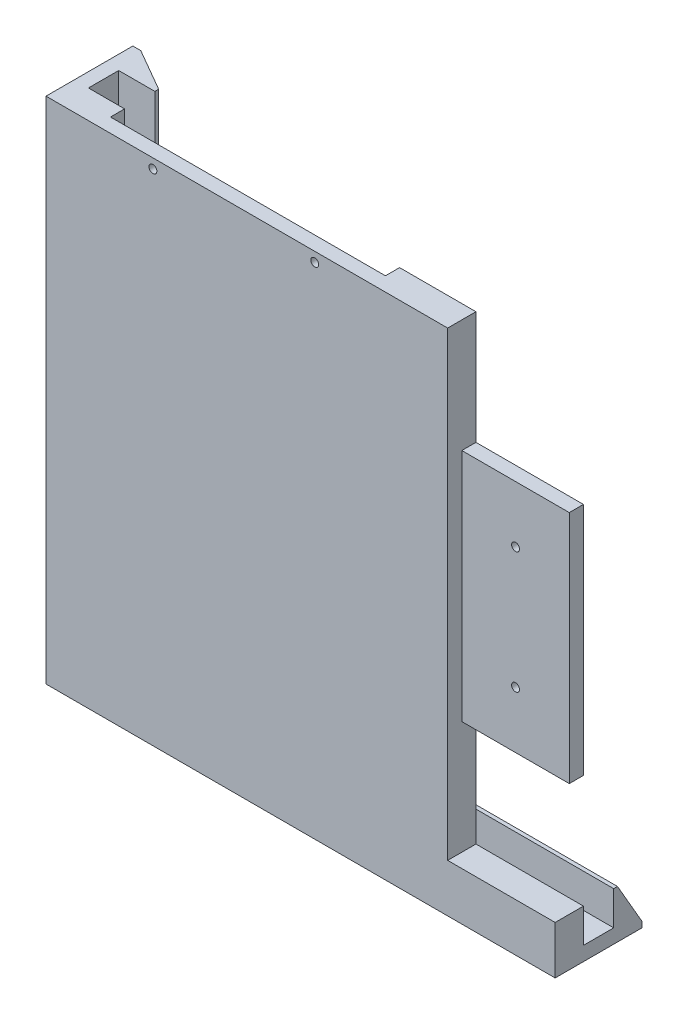
SolidWorks part; units mm, degrees
ref_plane "Alzado" through (0, 0, 0) normal (0, 0, 1) x (1, 0, 0)
ref_plane "Planta" through (0, 0, 0) normal (0, 1, 0) x (1, 0, 0)
ref_plane "Vista lateral" through (0, 0, 0) normal (1, 0, 0) x (0, 0, -1)
sketch "Croquis1" plane through (0, 0, 0) normal (0, 0, 1) x (1, 0, 0)
  line L1 (0, 0) -> (180, 0)
  line L2 (0, 0) -> (0, 180)
  line L3 (0, 180) -> (180, 180)
  line L4 (180, 0) -> (180, 180)
  dimension "D1" = 180
extrude "Saliente-Extruir1" add sketch "Croquis1" along normal blind 30.7
sketch "Croquis2" plane through (0, 0, 0) normal (0, 0, -1) x (-1, 0, 0)
  line L0 (-180, 0) -> (-180, 180) construction
  line L1 (-180, 17.01) -> (-17.79, 17.01)
  line L2 (-180, 17.01) -> (-180, 180)
  line L3 (-180, 180) -> (-17.79, 180)
  line L4 (-17.79, 17.01) -> (-17.79, 180)
  line L5 (-180, 180) -> (0, 180) construction
  line L6 (0, 180) -> (0, 0) construction
  line L7 (0, 0) -> (-180, 0) construction
  dimension "D1" = 17.79
  dimension "D2" = 17.01
extrude "Cortar-Extruir1" cut sketch "Croquis2" against normal blind 20.7
sketch "Croquis4" plane through (0, 180, 0) normal (0, 1, 0) x (1, 0, 0)
  line L0 (17.79, -20.7) -> (17.79, 0) construction
  line L1 (180, -20.7) -> (5, -20.7)
  line L2 (180, -20.7) -> (180, -10)
  line L3 (180, -10) -> (5, -10)
  line L4 (5, -20.7) -> (5, -10)
  dimension "D1" = 10.7
  dimension "D2" = 12.79
extrude "Cortar-Extruir2" cut sketch "Croquis4" against normal offset from surface (175 mm away) 5 up to face at (90, 0, 15.35)
sketch "Croquis5" plane through (0, 0, 20.7) normal (0, 0, -1) x (-1, 0, 0)
  line L0 (-180, 17.01) -> (-17.79, 17.01) construction
  line L1 (-142, 140) -> (-180, 140)
  line L2 (-142, 140) -> (-142, 180)
  line L3 (-142, 180) -> (-180, 180)
  line L4 (-180, 140) -> (-180, 180)
  line L5 (-142, 57.01) -> (-180, 57.01)
  line L6 (-142, 57.01) -> (-142, 17.01)
  line L7 (-142, 17.01) -> (-180, 17.01)
  line L8 (-180, 57.01) -> (-180, 17.01)
  line L9 (-180, 180) -> (-180, 5) construction
extrude "Cortar-Extruir3" cut sketch "Croquis5" against normal blind 10
sketch "Croquis6" plane through (0, 0, 30.7) normal (0, 0, 1) x (1, 0, 0)
  line L1 (180, 140) -> (142, 140)
  line L2 (180, 140) -> (180, 57.01)
  line L3 (180, 57.01) -> (142, 57.01)
  line L4 (142, 140) -> (142, 57.01)
extrude "Cortar-Extruir4" cut sketch "Croquis6" against normal blind 5
sketch "Croquis7" plane through (0, 0, 20.7) normal (0, 0, -1) x (-1, 0, 0)
  line L1 (-115, 173.2) -> (-17.79, 173.2)
  line L2 (-115, 173.2) -> (-115, 180)
  line L3 (-115, 180) -> (-17.79, 180)
  line L4 (-17.79, 173.2) -> (-17.79, 180)
extrude "Cortar-Extruir5" cut sketch "Croquis7" against normal blind 5
chamfer "Chaflán1" distance 15 angle 30 2 edges at (17.79, 98.505, 0) (98.895, 17.01, 0)
sketch "Croquis8" plane through (0, 0, 20.7) normal (0, 0, -1) x (-1, 0, 0)
  circle A0 centre (-37.79, 176.6) radius 1.4
  circle A1 centre (-95, 176.6) radius 1.4
  circle A2 centre (-161, 120) radius 1.4
  circle A3 centre (-161, 77.01) radius 1.4
extrude "Cortar-Extruir6" cut sketch "Croquis8" against normal blind 20
